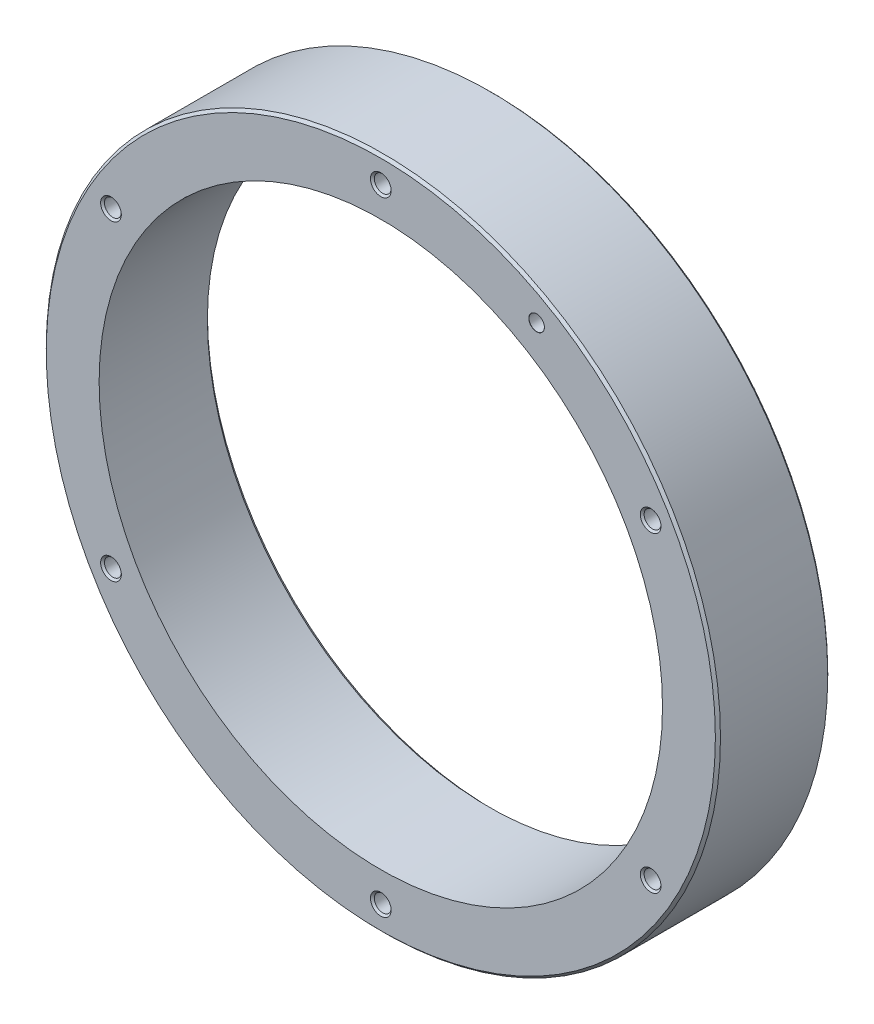
SolidWorks part; units mm, degrees
material "6061-T6 (SS)"
ref_plane "Front Plane" through (0, 0, 0) normal (0, 0, 1) x (1, 0, 0)
ref_plane "Top Plane" through (0, 0, 0) normal (0, 1, 0) x (1, 0, 0)
ref_plane "Right Plane" through (0, 0, 0) normal (1, 0, 0) x (0, 0, -1)
sketch "Sketch1" plane through (0, 0, 0) normal (0, 0, 1) x (1, 0, 0)
  circle A0 centre (0, 0) radius 55.15
  circle A1 centre (0, 0) radius 66
  dimension "D1" = 110.3
  dimension "D2" = 132
extrude "Collar_Body" add sketch "Sketch1" against normal blind 22
hole_wizard "M4x0.7 Bottoming Tapped Hole1" positions "Sketch4" profile "Sketch5" tap size "M4x0.7" standard "HASCO Metric"
sketch "Sketch4" plane through (0, 0, 0) normal (0, 0, 1) x (1, 0, 0)
  point P0 (0, 61)
  dimension "D1" = 61
sketch "Sketch5" plane through (0, 61, 0) normal (1, 0, 0) x (0, -1, 0)
  line L0 (0, 0) -> (0, 11.9914)
  line L1 (0, 11.9914) -> (1.65, 11)
  line L2 (1.65, 11) -> (1.65, 0.375)
  line L3 (1.65, 0.375) -> (2.025, 0)
  line L5 (2.025, 0) -> (0, 0)
  line L6 (-1.65, 0.375) -> (-2.025, 0) construction
  line L10 (0, 11.9914) -> (-1.65, 11) construction
  line L11 (0, -6.35) -> (0, 107.95) construction
  dimension "Tap Drill Dia." = 3.3
  dimension "Tap Drill Depth" = 11
  dimension "Near C'Sink Dia." = 4.05
  dimension "Near C'Sink Angle" = 90
  dimension "Drill Angle" = 118
cosmetic thread "Hole Thread1" parameters "D1"=8, "D2"=4
sketch "Sketch6" plane through (0, 0, 0) normal (1, 0, 0) x (0, 0, -1)
  line L0 (9.7183, 0) -> (13.5633, 0) construction
pattern_circular "M4pattern" count 6 over 360 about axis through (0, 0, 0) along (0, 0, 1) of "M4x0.7 Bottoming Tapped Hole1"
cosmetic thread "Hole Thread2" parameters "D1"=8, "D2"=4
cosmetic thread "Hole Thread3" parameters "D1"=8, "D2"=4
cosmetic thread "Hole Thread4" parameters "D1"=8, "D2"=4
cosmetic thread "Hole Thread5" parameters "D1"=8, "D2"=4
cosmetic thread "Hole Thread6" parameters "D1"=8, "D2"=4
hole_wizard "Ø3.0mm Dowel Hole5" positions "Sketch7" profile "Sketch8" hole size "Ø3.0" standard "IS"
sketch "Sketch7" plane through (0, 0, 0) normal (0, 0, 1) x (1, 0, 0)
  line L0 (0, 0) -> (0, 14.5559) construction
  line L1 (0, 0) -> (30.5, 52.8275) construction
  point P6 (30.5, 52.8275)
  dimension "D1" = 30
  dimension "D2" = 61
sketch "Sketch8" plane through (30.5, 52.8275, 0) normal (1, 0, 0) x (0, -1, 0)
  line L0 (0, 0) -> (0, 7.9013)
  line L1 (0, 7.9013) -> (1.5, 7)
  line L2 (1.5, 7) -> (1.5, 0.025)
  line L3 (1.5, 0.025) -> (1.525, 0)
  line L5 (1.525, 0) -> (0, 0)
  line L6 (-1.5, 0.025) -> (-1.525, 0) construction
  line L10 (0, 7.9013) -> (-1.5, 7) construction
  line L11 (0, -6.35) -> (0, 107.95) construction
  dimension "Hole Dia." = 3
  dimension "Hole Depth" = 7
  dimension "Near C'Sink Dia." = 3.05
  dimension "Near C'Sink Angle" = 90
  dimension "Drill Angle" = 118
chamfer "Chamfer1" distance 0.5 angle 45 2 edges at (66, 0, -22) (66, 0, 0)
chamfer "Chamfer2" distance 0.8 angle 45 1 edges at (55.15, 0, -22)
equation "\"collar od\"= 132mm"
equation "\"collar id\"= 110.3mm"
equation "\"collar l\"= 22mm"
equation "\"bcd\"= 122mm"
equation "\"D2@Sketch1\"=\"collar od\""
equation "\"D1@Sketch1\"=\"collar id\""
equation "\"D1@Collar_Body\"=\"collar l\""
equation "\"D1@Sketch4\"=\"bcd\"/2"
equation "\"D2@Sketch7\"=\"bcd\"/2"
